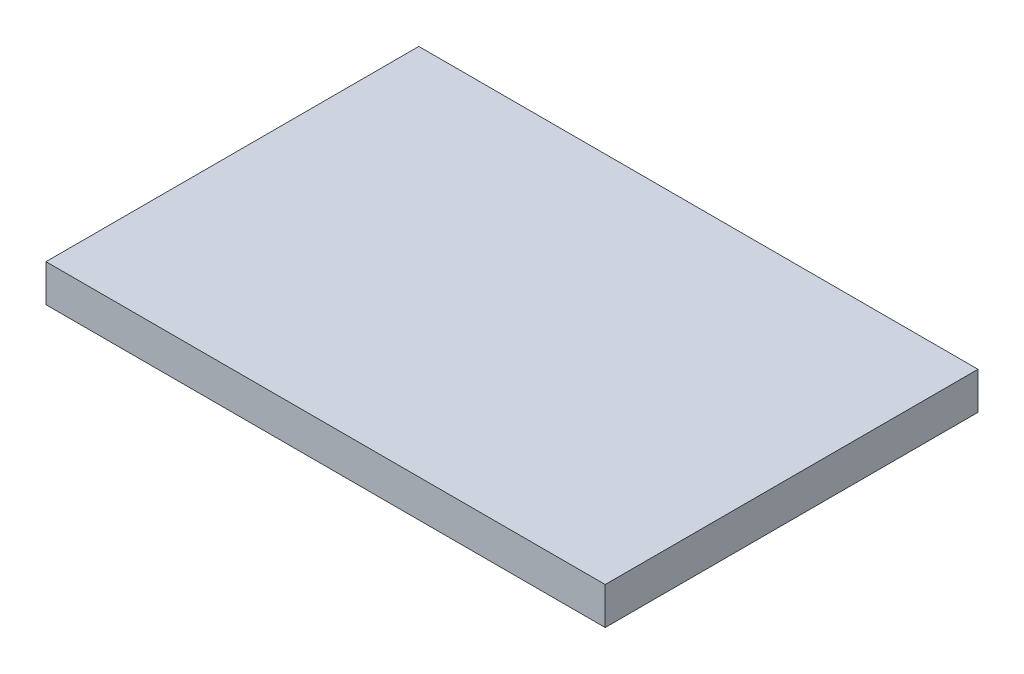
SolidWorks part; units mm, degrees
ref_plane "Plano frontal" through (0, 0, 0) normal (0, 0, 1) x (1, 0, 0)
ref_plane "Plano superior" through (0, 0, 0) normal (0, 1, 0) x (1, 0, 0)
ref_plane "Plano direito" through (0, 0, 0) normal (1, 0, 0) x (0, 0, -1)
sketch "Esboço1" plane through (0, 0, 0) normal (0, 1, 0) x (1, 0, 0)
  line L1 (-225, 150) -> (225, 150)
  line L2 (-225, 150) -> (-225, -150)
  line L3 (-225, -150) -> (225, -150)
  line L4 (225, 150) -> (225, -150)
  line L5 (-225, 150) -> (225, -150) construction
  line L6 (-225, -150) -> (225, 150) construction
  point P0 (0, 0)
  dimension "D1" = 450
  dimension "D2" = 300
extrude "Ressalto-extrusão1" add sketch "Esboço1" along normal blind 30
